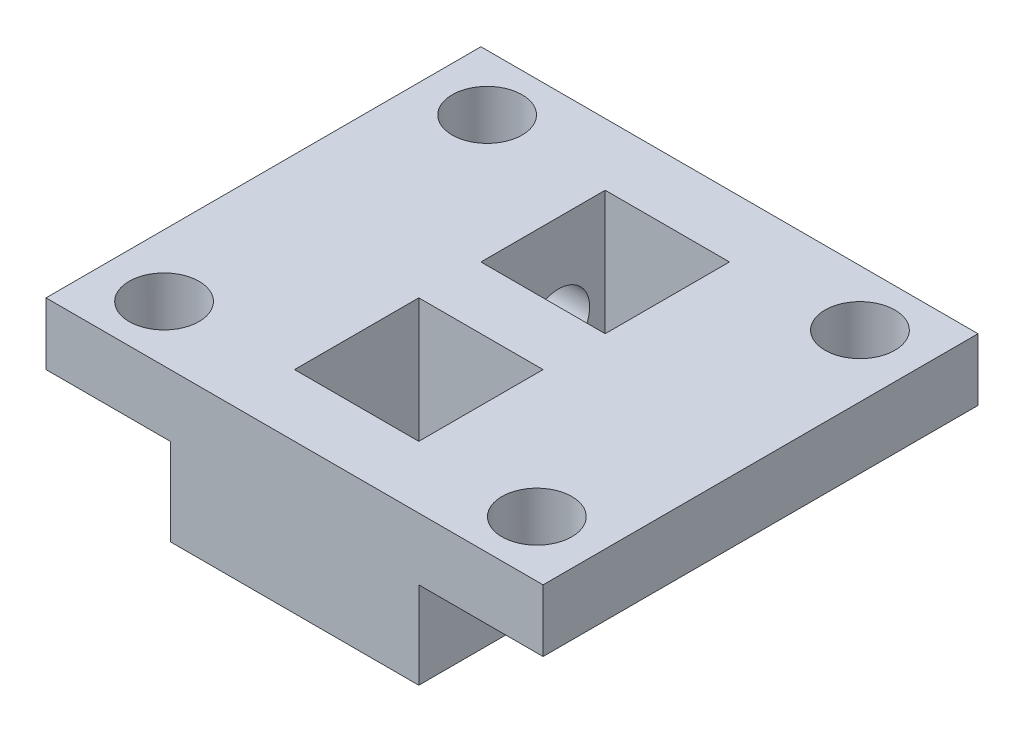
SolidWorks part; units mm, degrees
ref_plane "Front Plane" through (0, 0, 0) normal (0, 0, 1) x (1, 0, 0)
ref_plane "Top Plane" through (0, 0, 0) normal (0, 1, 0) x (1, 0, 0)
ref_plane "Right Plane" through (0, 0, 0) normal (1, 0, 0) x (0, 0, -1)
sketch "Sketch1" plane through (0, 0, 0) normal (0, 0, 1) x (1, 0, 0)
  line L0 (0, 0) -> (0, 7.62)
  line L1 (0, 7.62) -> (12.7, 7.62)
  line L2 (12.7, 7.62) -> (12.7, 4.445)
  line L3 (12.7, 4.445) -> (6.35, 4.445)
  line L4 (6.35, 4.445) -> (6.35, 0)
  line L5 (6.35, 0) -> (0, 0)
  dimension "D1" = 12.7
  dimension "D2" = 7.62
  dimension "D3" = 3.175
  dimension "D4" = 6.35
extrude "Boss-Extrude1" add sketch "Sketch1" along normal blind 11.1125 contours L0 L1 L2 L3 L4 L5
mirror "Mirror1" about plane through (0, 0, 11.1125) normal (-1, 0, 0) of bodies 101
sketch "Sketch2" plane through (-6.35, 0, 0) normal (-1, 0, 0) x (0, 0, 1)
  line L1 (5.5562, 2.8575) -> (0, 0) construction
  line L2 (5.5562, 2.8575) -> (11.1125, 0) construction
  line L5 (11.1125, 4.445) -> (0, 4.445) construction
  circle A0 centre (5.5562, 2.8575) radius 1.5875
  dimension "D1" = 3.175
sketch "Sketch3" plane through (0, 7.62, 0) normal (0, 1, 0) x (1, 0, 0)
  line L0 (-3.175, -3.175) -> (0, 0) construction
  line L1 (-12.7, 0) -> (12.7, 0) construction
  line L2 (0, 0) -> (3.175, -3.175) construction
  line L16 (-12.7, -9.525) -> (12.7, -9.525)
  line L20 (-3.175, -3.175) -> (-3.175, -9.525)
  line L21 (3.175, -3.175) -> (-3.175, -3.175)
  line L22 (3.175, -9.525) -> (3.175, -3.175)
  line L23 (-3.175, -9.525) -> (3.175, -9.525)
  point P2 (0, 0)
  dimension "D1" = 6.35
  dimension "D3" = 6.35
  dimension "D2" = 1.5875
extrude "Cut-Extrude1" cut sketch "Sketch3" against normal offset from surface (6.35 mm away) 1.27 up to face at (0, 0, 5.5562)
extrude "Cut-Extrude2" cut sketch "Sketch2" against normal up to surface (3.175 mm away) up to face at (-3.175, 4.445, 6.35)
sketch "Sketch4" plane through (0, 4.445, 0) normal (0, -1, 0) x (1, 0, 0)
  line L0 (9.525, 2.8575) -> (-9.525, 2.8575) construction
  line L1 (9.525, 2.8575) -> (12.7, 2.8575) construction
  line L2 (-9.525, 2.8575) -> (-12.7, 2.8575) construction
  line L4 (-12.7, 11.1125) -> (-12.7, 0) construction
  line L5 (12.7, 11.1125) -> (12.7, 0) construction
  line L6 (12.7, 11.1125) -> (6.35, 11.1125) construction
  circle A0 centre (9.525, 2.8575) radius 1.7859
  circle A1 centre (-9.525, 2.8575) radius 1.7859
  point P7 (0, 0)
  dimension "D1" = 3.5719
  dimension "D2" = 3.5719
  dimension "D3" = 8.255
  dimension "D4" = 3.175
extrude "Cut-Extrude3" cut sketch "Sketch4" against normal up to next
mirror "Mirror2" about plane through (0, 0, 11.1125) normal (0, 0, -1) of bodies 106 104
